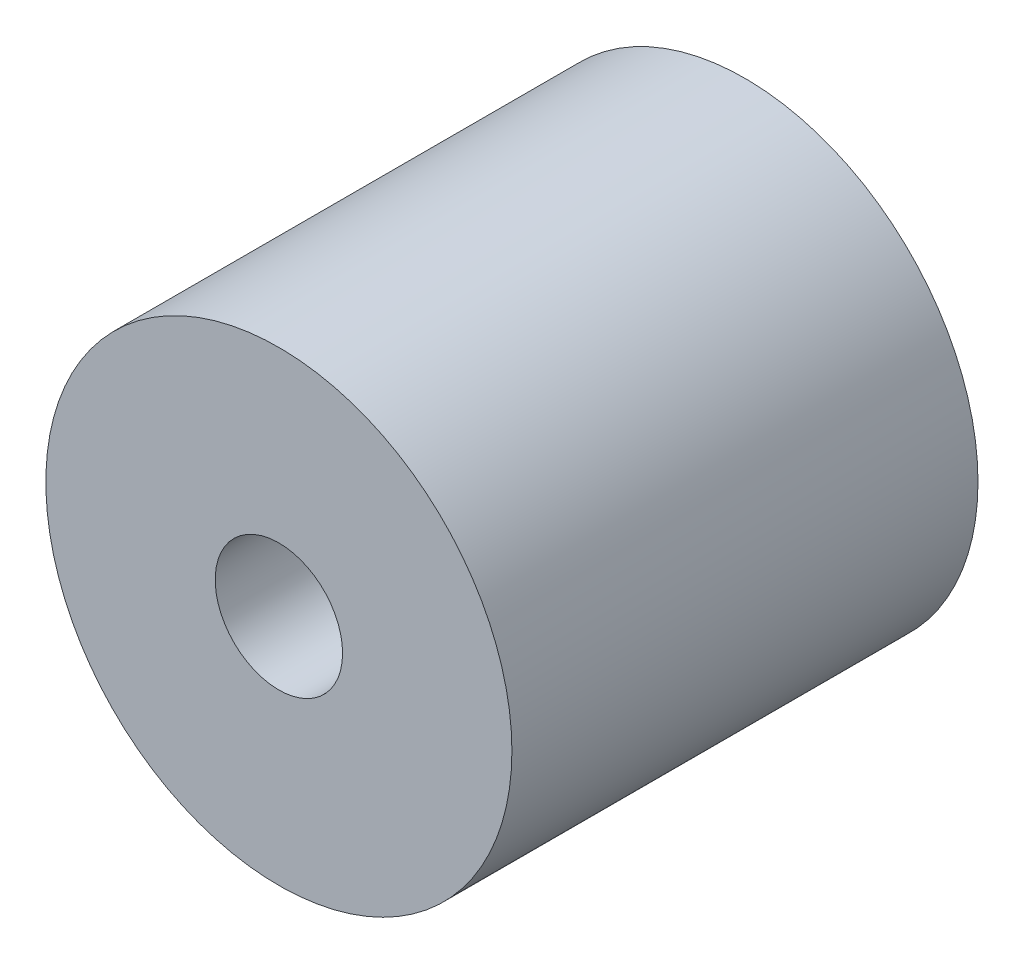
SolidWorks part; units mm, degrees
ref_plane "正面" through (0, 0, 0) normal (0, 0, 1) x (1, 0, 0)
ref_plane "平面" through (0, 0, 0) normal (0, 1, 0) x (1, 0, 0)
ref_plane "右側面" through (0, 0, 0) normal (1, 0, 0) x (0, 0, -1)
sketch "ｽｹｯﾁ2" plane through (0, 0, 0) normal (0, 0, 1) x (1, 0, 0)
  circle A0 centre (0, 0) radius 15
  circle A1 centre (0, 0) radius 4.1
  dimension "D1" = 8.2
  dimension "D2" = 30
extrude "ﾎﾞｽ - 押し出し1" add sketch "ｽｹｯﾁ2" along normal blind 30
